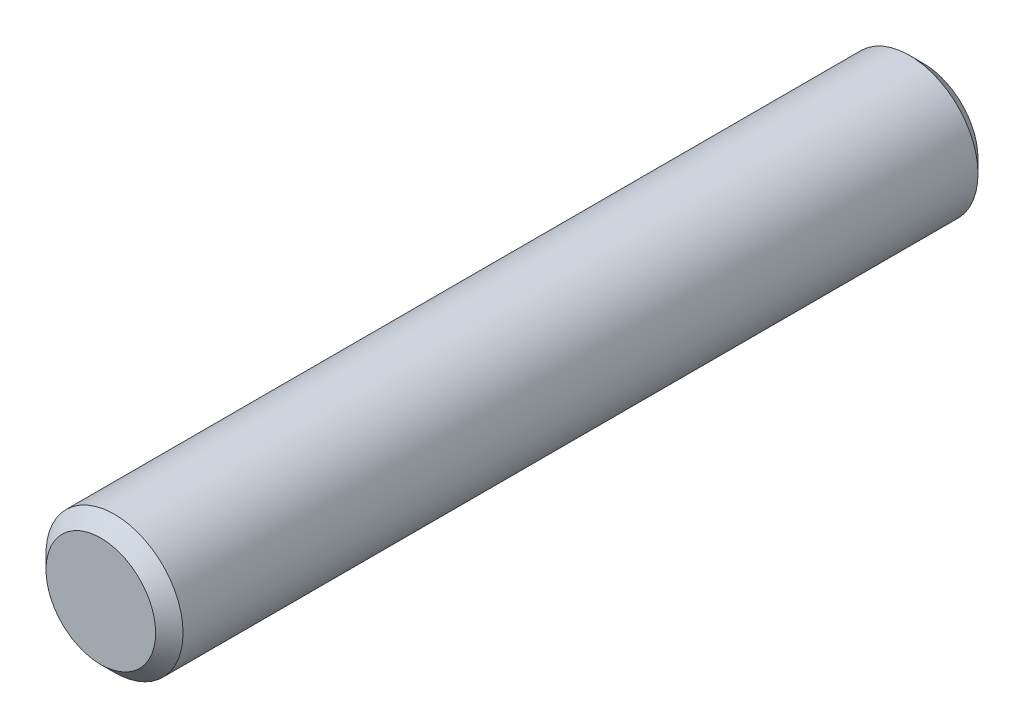
SolidWorks part; units mm, degrees
ref_plane "Спереди" through (0, 0, 0) normal (0, 0, 1) x (1, 0, 0)
ref_plane "Сверху" through (0, 0, 0) normal (0, 1, 0) x (1, 0, 0)
ref_plane "Справа" through (0, 0, 0) normal (1, 0, 0) x (0, 0, -1)
sketch "Эскиз1" plane through (0, 0, 0) normal (0, 0, 1) x (1, 0, 0)
  circle A0 centre (0, 0) radius 5
extrude "Бобышка-Вытянуть1" add sketch "Эскиз1" along normal blind 60
chamfer "Фаска1" distance 1 angle 45 2 edges at (5, 0, 0) (5, 0, 60)
